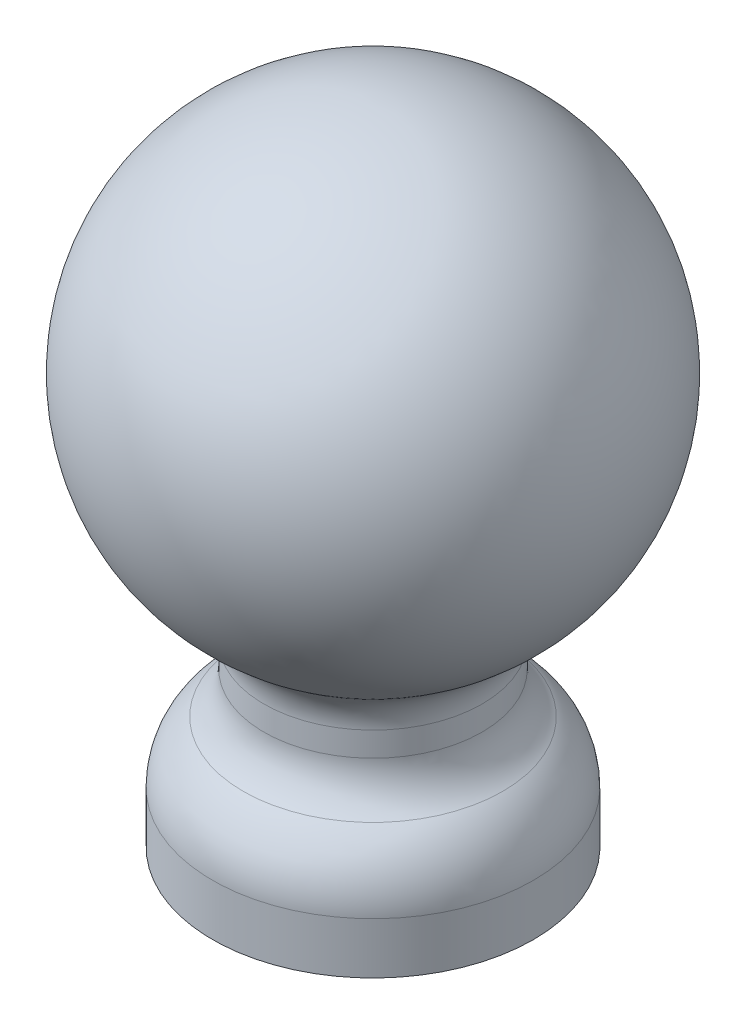
SolidWorks part; units mm, degrees
material "Porcelana ceramiczna"
ref_plane "Płaszczyzna przednia" through (0, 0, 0) normal (0, 0, 1) x (1, 0, 0)
ref_plane "Płaszczyzna górna" through (0, 0, 0) normal (0, 1, 0) x (1, 0, 0)
ref_plane "Płaszczyzna prawa" through (0, 0, 0) normal (1, 0, 0) x (0, 0, -1)
sketch "Szkic1" plane through (0, 0, 0) normal (0, 0, 1) x (1, 0, 0)
  line L0 (0, 0) -> (0, 50) construction
  line L1 (0, 0) -> (12.5, 0)
  line L2 (12.5, 0) -> (12.5, 8)
  line L3 (8.5, 12) -> (8.5, 13.8961)
  line L4 (0, 50) -> (-55.5019, 50) construction
  line L5 (0, 0) -> (0, 50)
  arc A0 (12.5, 8) -> (8.5, 12) centre (12.5, 12) cw
  arc A1 (8.5, 13.8961) -> (10.2273, 17.1877) centre (12.5, 13.8961) cw
  arc A2 (10.2273, 17.1877) -> (0, 50) centre (0, 32) ccw
  point P1 (13.8328, 0)
  point P12 (0, 87.3036)
  point P14 (8.1187, 23.5805)
  dimension "D1" = 18
  dimension "D3" = 4
  dimension "D2" = 25
  dimension "D4" = 8
  dimension "D5" = 50
revolve "Obrót1" add sketch "Szkic1" angle 360 about L5
fillet "Zaokrąglenie1" radius 6 1 edges at (12.5, 8, 0)
hole_wizard "Otwór gwintowany M51" positions "Szkic2" profile "Szkic3" tap size "M5" standard "ISO"
sketch "Szkic2" plane through (0, 0, 0) normal (0, -1, 0) x (-1, 0, 0)
  point P0 (0, 0)
  point P3 (0, 0)
sketch "Szkic3" plane through (0, 0, 0) normal (1, 0, 0) x (0, 0, -1)
  line L0 (0, 0) -> (0, 15.2618)
  line L1 (0, 15.2618) -> (2.1, 14)
  line L2 (2.1, 14) -> (2.1, 0)
  line L5 (2.1, 0) -> (0, 0)
  line L10 (0, 15.2618) -> (-2.1, 14) construction
  line L11 (0, -6.35) -> (0, 107.95) construction
  dimension "Średnica wiertła gwintu" = 4.2
  dimension "Głębokość otworu gwintowanego" = 14
  dimension "Kąt wiertła" = 118
cosmetic thread "Gwint otworu1" parameters "D1"=10, "D2"=5
